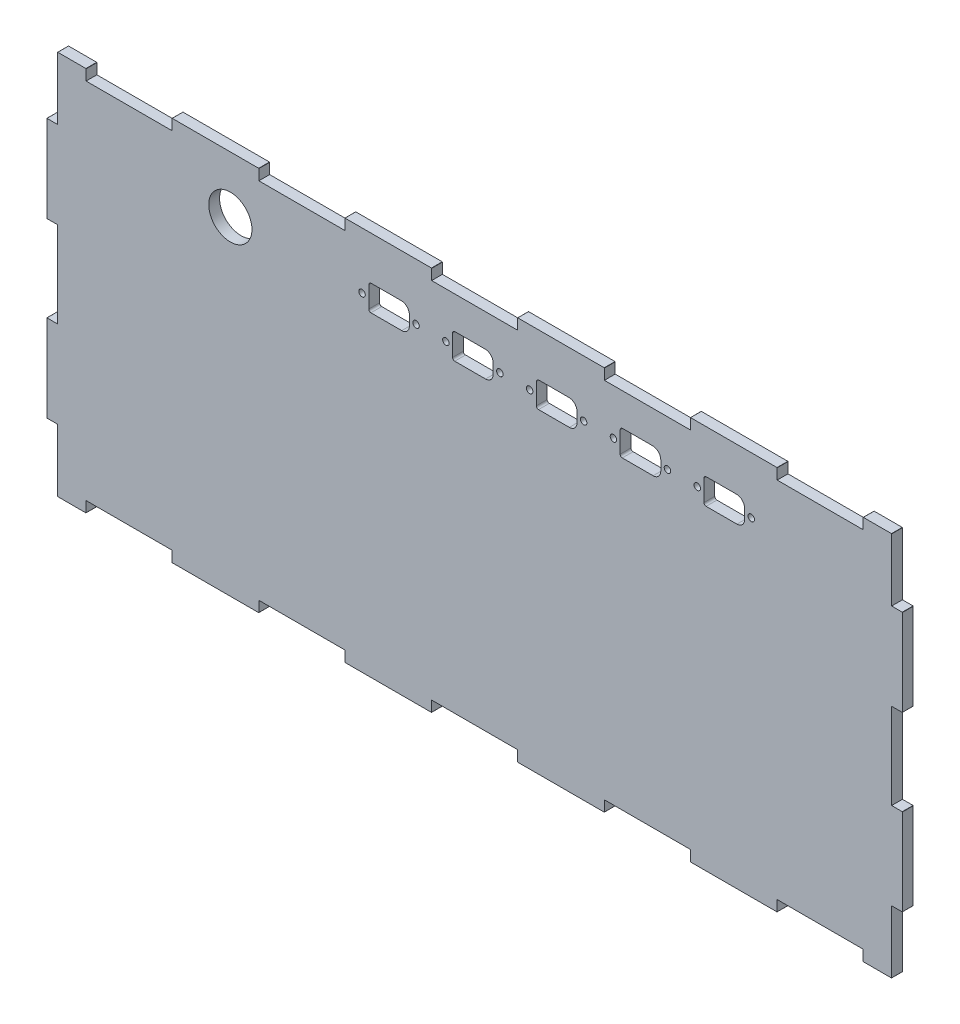
SolidWorks part; units mm, degrees
ref_plane "Front Plane" through (0, 0, 0) normal (0, 0, 1) x (1, 0, 0)
ref_plane "Top Plane" through (0, 0, 0) normal (0, 1, 0) x (1, 0, 0)
ref_plane "Right Plane" through (0, 0, 0) normal (1, 0, 0) x (0, 0, -1)
sketch "Model" plane through (0, 0, 0) normal (0, 0, 1) x (1, 0, 0)
  line L0 (-179.94, -89.08) -> (-179.93, -89.07)
  line L1 (-179.93, -89.07) -> (-179.92, -89.05)
  line L2 (-179.92, -89.05) -> (-179.91, -89.04)
  line L3 (-179.91, -89.04) -> (-179.9, -89.02)
  line L4 (-179.9, -89.02) -> (-179.9, -84.1)
  line L5 (-179.9, -84.1) -> (-140.1, -84.1)
  line L6 (-140.1, -84.1) -> (-140.1, -89.02)
  line L7 (-140.1, -89.02) -> (-140.08, -89.06)
  line L8 (-140.08, -89.06) -> (-140.07, -89.07)
  line L9 (-140.07, -89.07) -> (-140.05, -89.08)
  line L10 (-140.05, -89.08) -> (-140.04, -89.09)
  line L11 (-140.04, -89.09) -> (-140.02, -89.1)
  line L12 (-140.02, -89.1) -> (-99.98, -89.1)
  line L13 (-99.98, -89.1) -> (-99.94, -89.08)
  line L14 (-99.94, -89.08) -> (-99.93, -89.07)
  line L15 (-99.93, -89.07) -> (-99.92, -89.05)
  line L16 (-99.92, -89.05) -> (-99.91, -89.04)
  line L17 (-99.91, -89.04) -> (-99.9, -89.02)
  line L18 (-99.9, -89.02) -> (-99.9, -84.1)
  line L19 (-99.9, -84.1) -> (-60.1, -84.1)
  line L20 (-60.1, -84.1) -> (-60.1, -89.02)
  line L21 (-60.1, -89.02) -> (-60.08, -89.06)
  line L22 (-60.08, -89.06) -> (-60.07, -89.07)
  line L23 (-60.07, -89.07) -> (-60.05, -89.08)
  line L24 (-60.05, -89.08) -> (-60.04, -89.09)
  line L25 (-60.04, -89.09) -> (-60.02, -89.1)
  line L26 (-60.02, -89.1) -> (-19.98, -89.1)
  line L27 (-19.98, -89.1) -> (-19.94, -89.08)
  line L28 (-19.94, -89.08) -> (-19.93, -89.07)
  line L29 (-19.93, -89.07) -> (-19.92, -89.05)
  line L30 (-19.92, -89.05) -> (-19.91, -89.04)
  line L31 (-19.91, -89.04) -> (-19.9, -89.02)
  line L32 (-19.9, -89.02) -> (-19.9, -84.1)
  line L33 (-19.9, -84.1) -> (19.9, -84.1)
  line L34 (19.9, -84.1) -> (19.9, -89.02)
  line L35 (19.9, -89.02) -> (19.92, -89.06)
  line L36 (19.92, -89.06) -> (19.93, -89.07)
  line L37 (19.93, -89.07) -> (19.95, -89.08)
  line L38 (19.95, -89.08) -> (19.96, -89.09)
  line L39 (19.96, -89.09) -> (19.98, -89.1)
  line L40 (19.98, -89.1) -> (60.02, -89.1)
  line L41 (60.02, -89.1) -> (60.06, -89.08)
  line L42 (60.06, -89.08) -> (60.07, -89.07)
  line L43 (60.07, -89.07) -> (60.08, -89.05)
  line L44 (60.08, -89.05) -> (60.09, -89.04)
  line L45 (60.09, -89.04) -> (60.1, -89.02)
  line L46 (60.1, -89.02) -> (60.1, -84.1)
  line L47 (60.1, -84.1) -> (99.9, -84.1)
  line L48 (99.9, -84.1) -> (99.9, -89.02)
  line L49 (99.9, -89.02) -> (99.92, -89.06)
  line L50 (99.92, -89.06) -> (99.93, -89.07)
  line L51 (99.93, -89.07) -> (99.95, -89.08)
  line L52 (99.95, -89.08) -> (99.96, -89.09)
  line L53 (99.96, -89.09) -> (99.98, -89.1)
  line L54 (99.98, -89.1) -> (140.02, -89.1)
  line L55 (140.02, -89.1) -> (140.06, -89.08)
  line L56 (140.06, -89.08) -> (140.07, -89.07)
  line L57 (140.07, -89.07) -> (140.08, -89.05)
  line L58 (140.08, -89.05) -> (140.09, -89.04)
  line L59 (140.09, -89.04) -> (140.1, -89.02)
  line L60 (140.1, -89.02) -> (140.1, -84.1)
  line L61 (140.1, -84.1) -> (179.9, -84.1)
  line L62 (179.9, -84.1) -> (179.9, -89.02)
  line L63 (179.9, -89.02) -> (179.92, -89.06)
  line L64 (179.92, -89.06) -> (179.93, -89.07)
  line L65 (179.93, -89.07) -> (179.95, -89.08)
  line L66 (179.95, -89.08) -> (179.96, -89.09)
  line L67 (179.96, -89.09) -> (179.98, -89.1)
  line L68 (179.98, -89.1) -> (193.02, -89.1)
  line L69 (193.02, -89.1) -> (193.06, -89.08)
  line L70 (193.06, -89.08) -> (193.07, -89.07)
  line L71 (193.07, -89.07) -> (193.08, -89.05)
  line L72 (193.08, -89.05) -> (193.09, -89.04)
  line L73 (193.09, -89.04) -> (193.1, -89.02)
  line L74 (193.1, -89.02) -> (193.1, -60.1)
  line L75 (193.1, -60.1) -> (198.02, -60.1)
  line L76 (198.02, -60.1) -> (198.06, -60.08)
  line L77 (198.06, -60.08) -> (198.07, -60.07)
  line L78 (198.07, -60.07) -> (198.08, -60.05)
  line L79 (198.08, -60.05) -> (198.09, -60.04)
  line L80 (198.09, -60.04) -> (198.1, -60.02)
  line L81 (198.1, -60.02) -> (198.1, -19.98)
  line L82 (198.1, -19.98) -> (198.08, -19.94)
  line L83 (198.08, -19.94) -> (198.07, -19.93)
  line L84 (198.07, -19.93) -> (198.05, -19.92)
  line L85 (198.05, -19.92) -> (198.04, -19.91)
  line L86 (198.04, -19.91) -> (198.02, -19.9)
  line L87 (198.02, -19.9) -> (193.1, -19.9)
  line L88 (193.1, -19.9) -> (193.1, 19.9)
  line L89 (193.1, 19.9) -> (198.02, 19.9)
  line L90 (198.02, 19.9) -> (198.06, 19.92)
  line L91 (198.06, 19.92) -> (198.07, 19.93)
  line L92 (198.07, 19.93) -> (198.08, 19.95)
  line L93 (198.08, 19.95) -> (198.09, 19.96)
  line L94 (198.09, 19.96) -> (198.1, 19.98)
  line L95 (198.1, 19.98) -> (198.1, 60.02)
  line L96 (198.1, 60.02) -> (198.08, 60.06)
  line L97 (198.08, 60.06) -> (198.07, 60.07)
  line L98 (198.07, 60.07) -> (198.05, 60.08)
  line L99 (198.05, 60.08) -> (198.04, 60.09)
  line L100 (198.04, 60.09) -> (198.02, 60.1)
  line L101 (198.02, 60.1) -> (193.1, 60.1)
  line L102 (193.1, 60.1) -> (193.1, 89.02)
  line L103 (193.1, 89.02) -> (193.08, 89.06)
  line L104 (193.08, 89.06) -> (193.07, 89.07)
  line L105 (193.07, 89.07) -> (193.05, 89.08)
  line L106 (193.05, 89.08) -> (193.04, 89.09)
  line L107 (193.04, 89.09) -> (193.02, 89.1)
  line L108 (193.02, 89.1) -> (179.98, 89.1)
  line L109 (179.98, 89.1) -> (179.94, 89.08)
  line L110 (179.94, 89.08) -> (179.93, 89.07)
  line L111 (179.93, 89.07) -> (179.92, 89.05)
  line L112 (179.92, 89.05) -> (179.91, 89.04)
  line L113 (179.91, 89.04) -> (179.9, 89.02)
  line L114 (179.9, 89.02) -> (179.9, 84.1)
  line L115 (179.9, 84.1) -> (140.1, 84.1)
  line L116 (140.1, 84.1) -> (140.1, 89.02)
  line L117 (140.1, 89.02) -> (140.08, 89.06)
  line L118 (140.08, 89.06) -> (140.07, 89.07)
  line L119 (140.07, 89.07) -> (140.05, 89.08)
  line L120 (140.05, 89.08) -> (140.04, 89.09)
  line L121 (140.04, 89.09) -> (140.02, 89.1)
  line L122 (140.02, 89.1) -> (99.98, 89.1)
  line L123 (99.98, 89.1) -> (99.94, 89.08)
  line L124 (99.94, 89.08) -> (99.93, 89.07)
  line L125 (99.93, 89.07) -> (99.92, 89.05)
  line L126 (99.92, 89.05) -> (99.91, 89.04)
  line L127 (99.91, 89.04) -> (99.9, 89.02)
  line L128 (99.9, 89.02) -> (99.9, 84.1)
  line L129 (99.9, 84.1) -> (60.1, 84.1)
  line L130 (60.1, 84.1) -> (60.1, 89.02)
  line L131 (60.1, 89.02) -> (60.08, 89.06)
  line L132 (60.08, 89.06) -> (60.07, 89.07)
  line L133 (60.07, 89.07) -> (60.05, 89.08)
  line L134 (60.05, 89.08) -> (60.04, 89.09)
  line L135 (60.04, 89.09) -> (60.02, 89.1)
  line L136 (60.02, 89.1) -> (19.98, 89.1)
  line L137 (19.98, 89.1) -> (19.94, 89.08)
  line L138 (19.94, 89.08) -> (19.93, 89.07)
  line L139 (19.93, 89.07) -> (19.92, 89.05)
  line L140 (19.92, 89.05) -> (19.91, 89.04)
  line L141 (19.91, 89.04) -> (19.9, 89.02)
  line L142 (19.9, 89.02) -> (19.9, 84.1)
  line L143 (19.9, 84.1) -> (-19.9, 84.1)
  line L144 (-19.9, 84.1) -> (-19.9, 89.02)
  line L145 (-19.9, 89.02) -> (-19.92, 89.06)
  line L146 (-19.92, 89.06) -> (-19.93, 89.07)
  line L147 (-19.93, 89.07) -> (-19.95, 89.08)
  line L148 (-19.95, 89.08) -> (-19.96, 89.09)
  line L149 (-19.96, 89.09) -> (-19.98, 89.1)
  line L150 (-19.98, 89.1) -> (-60.02, 89.1)
  line L151 (-60.02, 89.1) -> (-60.06, 89.08)
  line L152 (-60.06, 89.08) -> (-60.07, 89.07)
  line L153 (-60.07, 89.07) -> (-60.08, 89.05)
  line L154 (-60.08, 89.05) -> (-60.09, 89.04)
  line L155 (-60.09, 89.04) -> (-60.1, 89.02)
  line L156 (-60.1, 89.02) -> (-60.1, 84.1)
  line L157 (-60.1, 84.1) -> (-99.9, 84.1)
  line L158 (-99.9, 84.1) -> (-99.9, 89.02)
  line L159 (-99.9, 89.02) -> (-99.92, 89.06)
  line L160 (-99.92, 89.06) -> (-99.93, 89.07)
  line L161 (-99.93, 89.07) -> (-99.95, 89.08)
  line L162 (-99.95, 89.08) -> (-99.96, 89.09)
  line L163 (-99.96, 89.09) -> (-99.98, 89.1)
  line L164 (-99.98, 89.1) -> (-140.02, 89.1)
  line L165 (-140.02, 89.1) -> (-140.06, 89.08)
  line L166 (-140.06, 89.08) -> (-140.07, 89.07)
  line L167 (-140.07, 89.07) -> (-140.08, 89.05)
  line L168 (-140.08, 89.05) -> (-140.09, 89.04)
  line L169 (-140.09, 89.04) -> (-140.1, 89.02)
  line L170 (-140.1, 89.02) -> (-140.1, 84.1)
  line L171 (-140.1, 84.1) -> (-179.9, 84.1)
  line L172 (-179.9, 84.1) -> (-179.9, 89.02)
  line L173 (-179.9, 89.02) -> (-179.92, 89.06)
  line L174 (-179.92, 89.06) -> (-179.93, 89.07)
  line L175 (-179.93, 89.07) -> (-179.95, 89.08)
  line L176 (-179.95, 89.08) -> (-179.96, 89.09)
  line L177 (-179.96, 89.09) -> (-179.98, 89.1)
  line L178 (-179.98, 89.1) -> (-193.02, 89.1)
  line L179 (-193.02, 89.1) -> (-193.06, 89.08)
  line L180 (-193.06, 89.08) -> (-193.07, 89.07)
  line L181 (-193.07, 89.07) -> (-193.08, 89.05)
  line L182 (-193.08, 89.05) -> (-193.09, 89.04)
  line L183 (-193.09, 89.04) -> (-193.1, 89.02)
  line L184 (-193.1, 89.02) -> (-193.1, 60.1)
  line L185 (-193.1, 60.1) -> (-198.02, 60.1)
  line L186 (-198.02, 60.1) -> (-198.06, 60.08)
  line L187 (-198.06, 60.08) -> (-198.07, 60.07)
  line L188 (-198.07, 60.07) -> (-198.08, 60.05)
  line L189 (-198.08, 60.05) -> (-198.09, 60.04)
  line L190 (-198.09, 60.04) -> (-198.1, 60.02)
  line L191 (-198.1, 60.02) -> (-198.1, 19.98)
  line L192 (-198.1, 19.98) -> (-198.08, 19.94)
  line L193 (-198.08, 19.94) -> (-198.07, 19.93)
  line L194 (-198.07, 19.93) -> (-198.05, 19.92)
  line L195 (-198.05, 19.92) -> (-198.04, 19.91)
  line L196 (-198.04, 19.91) -> (-198.02, 19.9)
  line L197 (-198.02, 19.9) -> (-193.1, 19.9)
  line L198 (-193.1, 19.9) -> (-193.1, -19.9)
  line L199 (-193.1, -19.9) -> (-198.02, -19.9)
  line L200 (-198.02, -19.9) -> (-198.06, -19.92)
  line L201 (-198.06, -19.92) -> (-198.07, -19.93)
  line L202 (-198.07, -19.93) -> (-198.08, -19.95)
  line L203 (-198.08, -19.95) -> (-198.09, -19.96)
  line L204 (-198.09, -19.96) -> (-198.1, -19.98)
  line L205 (-198.1, -19.98) -> (-198.1, -60.02)
  line L206 (-198.1, -60.02) -> (-198.08, -60.06)
  line L207 (-198.08, -60.06) -> (-198.07, -60.07)
  line L208 (-198.07, -60.07) -> (-198.05, -60.08)
  line L209 (-198.05, -60.08) -> (-198.04, -60.09)
  line L210 (-198.04, -60.09) -> (-198.02, -60.1)
  line L211 (-198.02, -60.1) -> (-193.1, -60.1)
  line L212 (-193.1, -60.1) -> (-193.1, -89.02)
  line L213 (-193.1, -89.02) -> (-193.08, -89.06)
  line L214 (-193.08, -89.06) -> (-193.07, -89.07)
  line L215 (-193.07, -89.07) -> (-193.05, -89.08)
  line L216 (-193.05, -89.08) -> (-193.04, -89.09)
  line L217 (-193.04, -89.09) -> (-193.02, -89.1)
  line L218 (-193.02, -89.1) -> (-179.98, -89.1)
  line L219 (-179.98, -89.1) -> (-179.94, -89.08)
extrude "Boss-Extrude1" add sketch "Model" along normal blind 5
sketch "Sketch2" plane through (0, 0, 5) normal (0, 0, 1) x (1, 0, 0)
  line L5 (-30.2088, 62.97) -> (-10.2088, 62.97) construction
  line L13 (-33.7338, 57.12) -> (-48.0088, 57.12)
  line L14 (-47.8088, 69.02) -> (-33.9338, 69.02)
  line L15 (-49.0088, 58.12) -> (-49.0088, 67.82)
  line L16 (-30.2088, 60.645) -> (-30.2088, 65.295)
  line L17 (5.0662, 57.12) -> (-9.2088, 57.12)
  line L18 (-9.0088, 69.02) -> (4.8662, 69.02)
  line L19 (-10.2088, 58.12) -> (-10.2088, 67.82)
  line L20 (8.5912, 60.645) -> (8.5912, 65.295)
  line L21 (43.8662, 57.12) -> (29.5912, 57.12)
  line L22 (29.7912, 69.02) -> (43.6662, 69.02)
  line L23 (28.5912, 58.12) -> (28.5912, 67.82)
  line L24 (47.3912, 60.645) -> (47.3912, 65.295)
  line L25 (82.6662, 57.12) -> (68.3912, 57.12)
  line L26 (68.5912, 69.02) -> (82.4662, 69.02)
  line L27 (67.3912, 58.12) -> (67.3912, 67.82)
  line L28 (86.1912, 60.645) -> (86.1912, 65.295)
  line L37 (8.5912, 62.97) -> (28.5912, 62.97) construction
  line L38 (47.3912, 62.97) -> (67.3912, 62.97) construction
  line L39 (121.4662, 57.12) -> (107.1912, 57.12)
  line L40 (107.3912, 69.02) -> (121.2662, 69.02)
  line L45 (106.1912, 58.12) -> (106.1912, 67.82)
  line L46 (124.9912, 60.645) -> (124.9912, 65.295)
  line L47 (86.1912, 62.97) -> (106.1912, 62.97) construction
  line L48 (-52.1088, 62.97) -> (-49.0088, 62.97) construction
  line L49 (-13.3088, 62.97) -> (-10.2088, 62.97) construction
  line L50 (25.4912, 62.97) -> (28.5912, 62.97) construction
  line L51 (64.2912, 62.97) -> (67.3912, 62.97) construction
  line L52 (103.0912, 62.97) -> (106.1912, 62.97) construction
  line L53 (128.0912, 62.97) -> (193.1, 62.97) construction
  line L54 (193.1, 60.1) -> (193.1, 89.02) construction
  line L55 (193.1, 62.97) -> (193.1, 89.02) construction
  arc A12 (-30.2088, 60.645) -> (-33.7338, 57.12) centre (-33.7338, 60.645) cw
  arc A13 (-30.2088, 65.295) -> (-33.9338, 69.02) centre (-33.9338, 65.295) ccw
  arc A14 (-48.0088, 57.12) -> (-49.0088, 58.12) centre (-48.0088, 58.12) cw
  arc A15 (-49.0088, 67.82) -> (-47.8088, 69.02) centre (-47.8088, 67.82) cw
  arc A16 (8.5912, 60.645) -> (5.0662, 57.12) centre (5.0662, 60.645) cw
  arc A17 (8.5912, 65.295) -> (4.8662, 69.02) centre (4.8662, 65.295) ccw
  arc A18 (-9.2088, 57.12) -> (-10.2088, 58.12) centre (-9.2088, 58.12) cw
  arc A19 (-10.2088, 67.82) -> (-9.0088, 69.02) centre (-9.0088, 67.82) cw
  arc A20 (47.3912, 60.645) -> (43.8662, 57.12) centre (43.8662, 60.645) cw
  arc A21 (47.3912, 65.295) -> (43.6662, 69.02) centre (43.6662, 65.295) ccw
  arc A22 (29.5912, 57.12) -> (28.5912, 58.12) centre (29.5912, 58.12) cw
  arc A23 (28.5912, 67.82) -> (29.7912, 69.02) centre (29.7912, 67.82) cw
  arc A24 (86.1912, 60.645) -> (82.6662, 57.12) centre (82.6662, 60.645) cw
  arc A25 (86.1912, 65.295) -> (82.4662, 69.02) centre (82.4662, 65.295) ccw
  arc A26 (68.3912, 57.12) -> (67.3912, 58.12) centre (68.3912, 58.12) cw
  arc A27 (67.3912, 67.82) -> (68.5912, 69.02) centre (68.5912, 67.82) cw
  arc A40 (124.9912, 60.645) -> (121.4662, 57.12) centre (121.4662, 60.645) cw
  arc A41 (124.9912, 65.295) -> (121.2662, 69.02) centre (121.2662, 65.295) ccw
  arc A42 (107.1912, 57.12) -> (106.1912, 58.12) centre (107.1912, 58.12) cw
  arc A43 (106.1912, 67.82) -> (107.3912, 69.02) centre (107.3912, 67.82) cw
  circle A44 centre (-52.1088, 62.97) radius 1.5
  circle A45 centre (-27.1088, 62.97) radius 1.5
  circle A46 centre (-13.3088, 62.97) radius 1.5
  circle A47 centre (11.6912, 62.97) radius 1.5
  circle A48 centre (25.4912, 62.97) radius 1.5
  circle A49 centre (50.4912, 62.97) radius 1.5
  circle A50 centre (64.2912, 62.97) radius 1.5
  circle A51 centre (89.2912, 62.97) radius 1.5
  circle A52 centre (103.0912, 62.97) radius 1.5
  circle A53 centre (128.0912, 62.97) radius 1.5
  dimension "D7" = 3
  dimension "D9" = 3
  dimension "D1" = 20
  dimension "D2" = 20
  dimension "D3" = 20
  dimension "D4" = 20
  dimension "D5" = 25
extrude "Cut-Extrude1" cut sketch "Sketch2" against normal through all
sketch "Sketch3" plane through (0, 0, 5) normal (0, 0, 1) x (1, 0, 0)
  line L1 (-53.6088, 62.97) -> (-113.1, 62.97) construction
  circle A0 centre (-113.1, 62.97) radius 10
  circle A1 centre (-52.1088, 62.97) radius 1.5 construction
  dimension "D1" = 20
extrude "Cut-Extrude2" cut sketch "Sketch3" against normal through all
